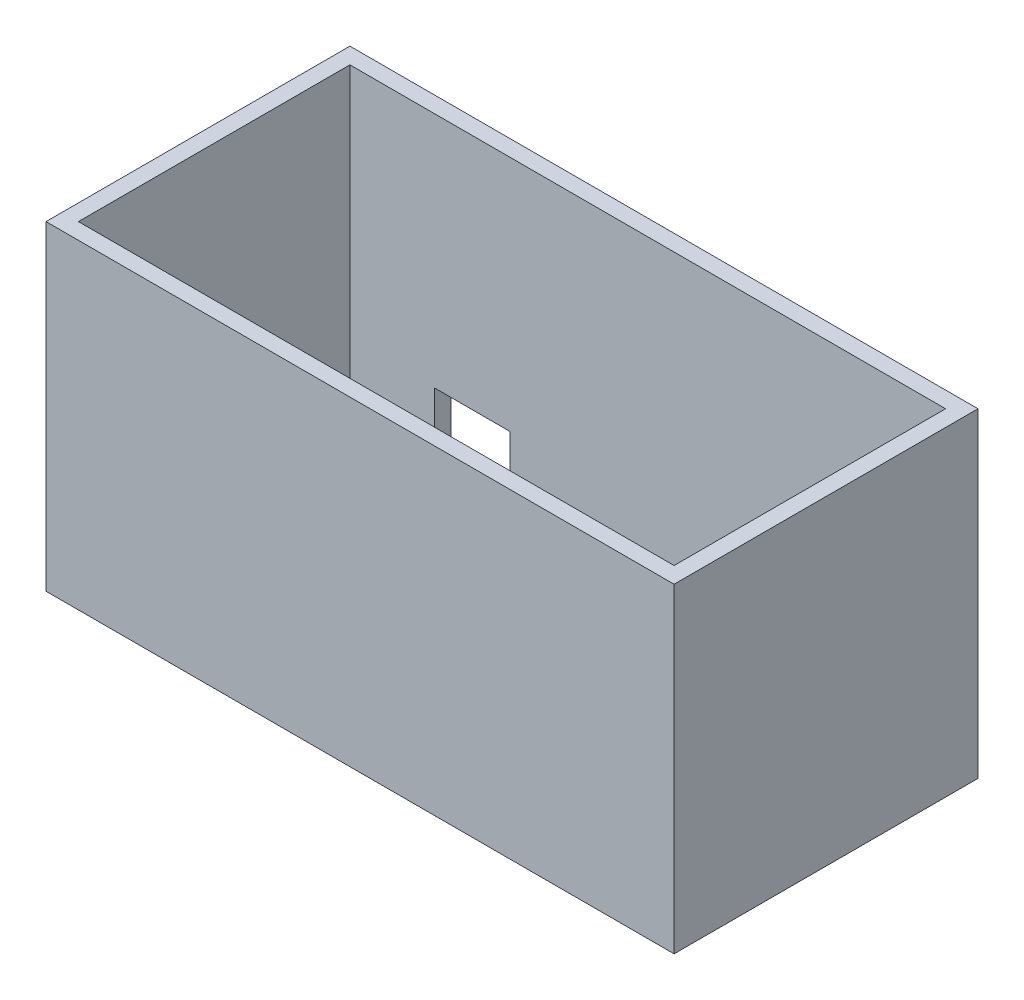
SolidWorks part; units mm, degrees
ref_plane "Front Plane" through (0, 0, 0) normal (0, 0, 1) x (1, 0, 0)
ref_plane "Top Plane" through (0, 0, 0) normal (0, 1, 0) x (1, 0, 0)
ref_plane "Right Plane" through (0, 0, 0) normal (1, 0, 0) x (0, 0, -1)
sketch "Sketch1" plane through (0, 0, 0) normal (0, 1, 0) x (1, 0, 0)
  line L1 (-98.425, -47.625) -> (98.425, -47.625)
  line L2 (-98.425, -47.625) -> (-98.425, 47.625)
  line L3 (-98.425, 47.625) -> (98.425, 47.625)
  line L4 (98.425, -47.625) -> (98.425, 47.625)
  line L5 (-98.425, -47.625) -> (98.425, 47.625) construction
  line L6 (-98.425, 47.625) -> (98.425, -47.625) construction
  point P0 (0, 0)
  dimension "D1" = 196.85
  dimension "D2" = 95.25
extrude "Boss-Extrude1" add sketch "Sketch1" along normal blind 5.08
sketch "Sketch2" plane through (0, 5.08, 0) normal (0, 1, 0) x (1, 0, 0)
  line L0 (98.425, 47.625) -> (98.425, -47.625)
  line L1 (98.425, -47.625) -> (-98.425, -47.625)
  line L2 (-98.425, -47.625) -> (-98.425, 47.625)
  line L3 (-98.425, 47.625) -> (98.425, 47.625)
  line L4 (-93.345, 42.545) -> (93.345, 42.545)
  line L5 (93.345, 42.545) -> (93.345, -42.545)
  line L6 (93.345, -42.545) -> (-93.345, -42.545)
  line L7 (-93.345, -42.545) -> (-93.345, 42.545)
  dimension "D1" = 5.08
extrude "Boss-Extrude2" add sketch "Sketch2" along normal blind 95.25
sketch "Sketch3" plane through (0, 0, -47.625) normal (0, 0, -1) x (-1, 0, 0)
  line L0 (66.7871, 5.6565) -> (66.7871, 25.9006)
  line L2 (66.7871, 25.9006) -> (43.1453, 25.9006)
  line L3 (43.1453, 25.9006) -> (43.1453, 5.6565)
  line L4 (43.1453, 5.6565) -> (66.7871, 5.6565)
  point P2 (57.3347, 26.0278)
  point P3 (80.9765, 5.7837)
extrude "Cut-Extrude2" cut sketch "Sketch3" against normal blind 7.62
